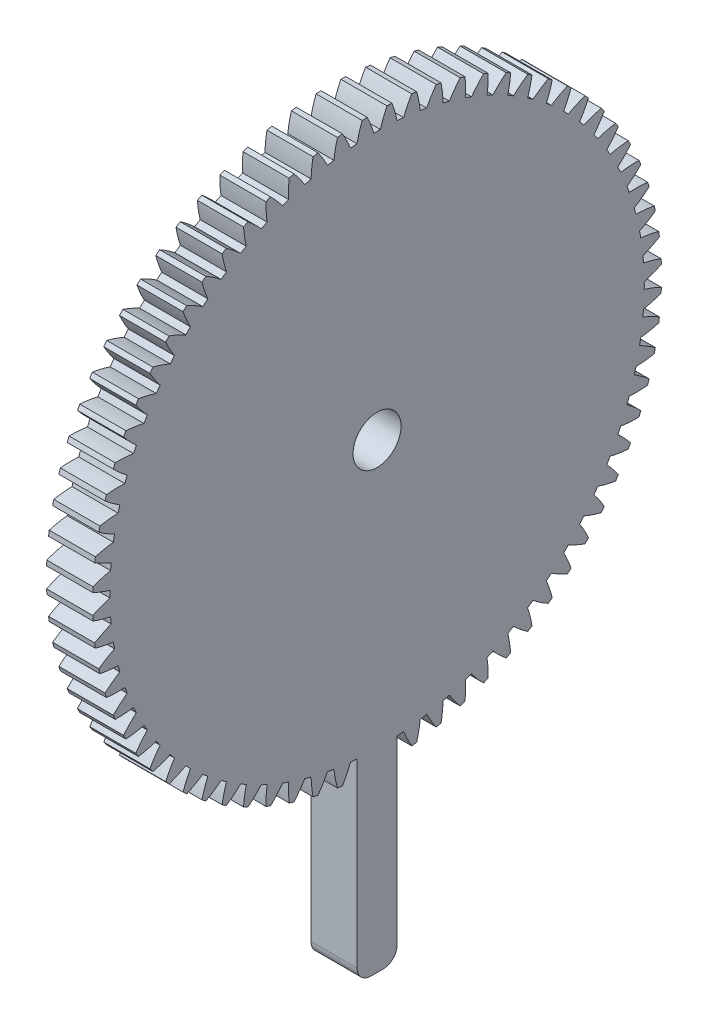
SolidWorks part; units mm, degrees
ref_plane "Front Plane" through (0, 0, 0) normal (0, 0, 1) x (1, 0, 0)
ref_plane "Top Plane" through (0, 0, 0) normal (0, 1, 0) x (1, 0, 0)
ref_plane "Right Plane" through (0, 0, 0) normal (1, 0, 0) x (0, 0, -1)
sketch "Sketch1" plane through (0, 0, 0) normal (0, 0, 1) x (1, 0, 0)
  line L0 (-10, 0) -> (60, 0) construction
  line L1 (0, 0) -> (0, 39.1583)
  line L2 (0, 0) -> (6.35, 0)
  line L3 (6.35, 0) -> (6.35, 39.1583)
  line L4 (6.35, 39.1583) -> (0, 39.1583)
  dimension "Diameter" = 78.3167
  dimension "Thickness" = 6.35
revolve "Revolve1" add sketch "Sketch1" angle 360 about L0
sketch "Sketch2" plane through (0, 0, 0) normal (-1, 0, 0) x (0, 0, 1)
  line L1 (0, 0) -> (0, 107) construction
  line L2 (0, 0) -> (-0.9058, 38.0892) construction
  line L3 (0, 0) -> (-3.3231, 76.1125) construction
  line L4 (-0.9058, 38.0892) -> (-1.6616, 38.0562) construction
  arc A0 (0.4536, 36.7764) -> (-0.4536, 36.7764) centre (0, 0) ccw
  arc A1 (1.3783, 39.1595) -> (-1.3783, 39.1595) centre (0, 0) ccw
  circle A2 centre (0, 0) radius 38.1 construction
  circle A3 centre (0, 0) radius 35.8023 construction
  arc A4 (-0.4536, 36.7764) -> (-1.3783, 39.1595) centre (-15.0738, 32.4744) ccw
  arc A5 (1.3783, 39.1595) -> (0.4536, 36.7764) centre (15.0738, 32.4744) ccw
  arc A6 (2.7534, 36.676) -> (2.0399, 39.1306) centre (-12.1861, 33.6646) ccw
  arc A7 (3.6571, 36.5969) -> (2.7534, 36.676) centre (0, 0) ccw
  arc A8 (4.786, 38.8903) -> (3.6571, 36.5969) centre (17.8467, 31.037) ccw
  arc A9 (4.786, 38.8903) -> (2.0399, 39.1306) centre (0, 0) ccw
  arc A10 (5.9395, 36.2965) -> (5.4426, 38.8039) centre (-9.2057, 34.5986) ccw
  arc A11 (6.8328, 36.1389) -> (5.9395, 36.2965) centre (0, 0) ccw
  arc A12 (8.1573, 38.3252) -> (6.8328, 36.1389) centre (20.4839, 29.3635) ccw
  arc A13 (8.1573, 38.3252) -> (5.4426, 38.8039) centre (0, 0) ccw
  arc A14 (9.0803, 35.6407) -> (8.8039, 38.1819) centre (-6.1552, 35.2692) ccw
  arc A15 (9.9566, 35.4059) -> (9.0803, 35.6407) centre (0, 0) ccw
  arc A16 (11.4665, 37.4684) -> (9.9566, 35.4059) centre (22.9651, 27.4665) ccw
  arc A17 (11.4665, 37.4684) -> (8.8039, 38.1819) centre (0, 0) ccw
  arc A18 (12.152, 34.7136) -> (12.0982, 37.2693) centre (-3.0578, 35.6715) ccw
  arc A19 (13.0045, 34.4034) -> (12.152, 34.7136) centre (0, 0) ccw
  arc A20 (14.6885, 36.3265) -> (13.0045, 34.4034) centre (25.2716, 25.3604) ccw
  arc A21 (14.6885, 36.3265) -> (12.0982, 37.2693) centre (0, 0) ccw
  arc A22 (15.1313, 33.5224) -> (15.3004, 36.073) centre (0.0628, 35.8022) ccw
  arc A23 (15.9535, 33.139) -> (15.1313, 33.5224) centre (0, 0) ccw
  arc A24 (17.7987, 34.9081) -> (15.9535, 33.139) centre (27.3857, 23.0613) ccw
  arc A25 (17.7987, 34.9081) -> (15.3004, 36.073) centre (0, 0) ccw
  arc A26 (17.9954, 32.0761) -> (18.3861, 34.6022) centre (3.1829, 35.6605) ccw
  arc A27 (18.781, 31.6225) -> (17.9954, 32.0761) centre (0, 0) ccw
  arc A28 (20.7734, 33.224) -> (18.781, 31.6225) centre (29.2915, 20.5867) ccw
  arc A29 (20.7734, 33.224) -> (18.3861, 34.6022) centre (0, 0) ccw
  arc A30 (20.7225, 30.3856) -> (21.3319, 32.8681) centre (6.2788, 35.2474) ccw
  arc A31 (21.4656, 29.8653) -> (20.7225, 30.3856) centre (0, 0) ccw
  arc A32 (23.59, 31.287) -> (21.4656, 29.8653) centre (30.9743, 17.9555) ccw
  arc A33 (23.59, 31.287) -> (21.3319, 32.8681) centre (0, 0) ccw
  arc A34 (23.292, 28.4639) -> (24.1154, 30.8838) centre (9.3269, 34.5661) ccw
  arc A35 (23.9869, 27.8808) -> (23.292, 28.4639) centre (0, 0) ccw
  arc A36 (26.227, 29.112) -> (23.9869, 27.8808) centre (32.4213, 15.1876) ccw
  arc A37 (26.227, 29.112) -> (24.1154, 30.8838) centre (0, 0) ccw
  arc A38 (25.6841, 26.3256) -> (26.7154, 28.6645) centre (12.3041, 33.6216) ccw
  arc A39 (26.3256, 25.6841) -> (25.6841, 26.3256) centre (0, 0) ccw
  arc A40 (28.6645, 26.7154) -> (26.3256, 25.6841) centre (33.6216, 12.3041) ccw
  arc A41 (28.6645, 26.7154) -> (26.7154, 28.6645) centre (0, 0) ccw
  arc A42 (27.8808, 23.9869) -> (29.112, 26.227) centre (15.1876, 32.4213) ccw
  arc A43 (28.4639, 23.292) -> (27.8808, 23.9869) centre (0, 0) ccw
  arc A44 (30.8838, 24.1154) -> (28.4639, 23.292) centre (34.5661, 9.3269) ccw
  arc A45 (30.8838, 24.1154) -> (29.112, 26.227) centre (0, 0) ccw
  arc A46 (29.8653, 21.4656) -> (31.287, 23.59) centre (17.9555, 30.9743) ccw
  arc A47 (30.3856, 20.7225) -> (29.8653, 21.4656) centre (0, 0) ccw
  arc A48 (32.8681, 21.3319) -> (30.3856, 20.7225) centre (35.2474, 6.2788) ccw
  arc A49 (32.8681, 21.3319) -> (31.287, 23.59) centre (0, 0) ccw
  arc A50 (31.6225, 18.781) -> (33.224, 20.7734) centre (20.5867, 29.2915) ccw
  arc A51 (32.0761, 17.9954) -> (31.6225, 18.781) centre (0, 0) ccw
  arc A52 (34.6022, 18.3861) -> (32.0761, 17.9954) centre (35.6605, 3.1829) ccw
  arc A53 (34.6022, 18.3861) -> (33.224, 20.7734) centre (0, 0) ccw
  arc A54 (33.139, 15.9535) -> (34.9081, 17.7987) centre (23.0613, 27.3857) ccw
  arc A55 (33.5224, 15.1313) -> (33.139, 15.9535) centre (0, 0) ccw
  arc A56 (36.073, 15.3004) -> (33.5224, 15.1313) centre (35.8022, 0.0628) ccw
  arc A57 (36.073, 15.3004) -> (34.9081, 17.7987) centre (0, 0) ccw
  arc A58 (34.4034, 13.0045) -> (36.3265, 14.6885) centre (25.3604, 25.2716) ccw
  arc A59 (34.7136, 12.152) -> (34.4034, 13.0045) centre (0, 0) ccw
  arc A60 (37.2693, 12.0982) -> (34.7136, 12.152) centre (35.6715, -3.0578) ccw
  arc A61 (37.2693, 12.0982) -> (36.3265, 14.6885) centre (0, 0) ccw
  arc A62 (35.4059, 9.9566) -> (37.4684, 11.4665) centre (27.4665, 22.9651) ccw
  arc A63 (35.6407, 9.0803) -> (35.4059, 9.9566) centre (0, 0) ccw
  arc A64 (38.1819, 8.8039) -> (35.6407, 9.0803) centre (35.2692, -6.1552) ccw
  arc A65 (38.1819, 8.8039) -> (37.4684, 11.4665) centre (0, 0) ccw
  arc A66 (36.1389, 6.8328) -> (38.3252, 8.1573) centre (29.3635, 20.4839) ccw
  arc A67 (36.2965, 5.9395) -> (36.1389, 6.8328) centre (0, 0) ccw
  arc A68 (38.8039, 5.4426) -> (36.2965, 5.9395) centre (34.5986, -9.2057) ccw
  arc A69 (38.8039, 5.4426) -> (38.3252, 8.1573) centre (0, 0) ccw
  arc A70 (36.5969, 3.6571) -> (38.8903, 4.786) centre (31.037, 17.8467) ccw
  arc A71 (36.676, 2.7534) -> (36.5969, 3.6571) centre (0, 0) ccw
  arc A72 (39.1306, 2.0399) -> (36.676, 2.7534) centre (33.6646, -12.1861) ccw
  arc A73 (39.1306, 2.0399) -> (38.8903, 4.786) centre (0, 0) ccw
  arc A74 (36.7764, 0.4536) -> (39.1595, 1.3783) centre (32.4744, 15.0738) ccw
  arc A75 (36.7764, -0.4536) -> (36.7764, 0.4536) centre (0, 0) ccw
  arc A76 (39.1595, -1.3783) -> (36.7764, -0.4536) centre (32.4744, -15.0738) ccw
  arc A77 (39.1595, -1.3783) -> (39.1595, 1.3783) centre (0, 0) ccw
  arc A78 (36.676, -2.7534) -> (39.1306, -2.0399) centre (33.6646, 12.1861) ccw
  arc A79 (36.5969, -3.6571) -> (36.676, -2.7534) centre (0, 0) ccw
  arc A80 (38.8903, -4.786) -> (36.5969, -3.6571) centre (31.037, -17.8467) ccw
  arc A81 (38.8903, -4.786) -> (39.1306, -2.0399) centre (0, 0) ccw
  arc A82 (36.2965, -5.9395) -> (38.8039, -5.4426) centre (34.5986, 9.2057) ccw
  arc A83 (36.1389, -6.8328) -> (36.2965, -5.9395) centre (0, 0) ccw
  arc A84 (38.3252, -8.1573) -> (36.1389, -6.8328) centre (29.3635, -20.4839) ccw
  arc A85 (38.3252, -8.1573) -> (38.8039, -5.4426) centre (0, 0) ccw
  arc A86 (35.6407, -9.0803) -> (38.1819, -8.8039) centre (35.2692, 6.1552) ccw
  arc A87 (35.4059, -9.9566) -> (35.6407, -9.0803) centre (0, 0) ccw
  arc A88 (37.4684, -11.4665) -> (35.4059, -9.9566) centre (27.4665, -22.9651) ccw
  arc A89 (37.4684, -11.4665) -> (38.1819, -8.8039) centre (0, 0) ccw
  arc A90 (34.7136, -12.152) -> (37.2693, -12.0982) centre (35.6715, 3.0578) ccw
  arc A91 (34.4034, -13.0045) -> (34.7136, -12.152) centre (0, 0) ccw
  arc A92 (36.3265, -14.6885) -> (34.4034, -13.0045) centre (25.3604, -25.2716) ccw
  arc A93 (36.3265, -14.6885) -> (37.2693, -12.0982) centre (0, 0) ccw
  arc A94 (33.5224, -15.1313) -> (36.073, -15.3004) centre (35.8022, -0.0628) ccw
  arc A95 (33.139, -15.9535) -> (33.5224, -15.1313) centre (0, 0) ccw
  arc A96 (34.9081, -17.7987) -> (33.139, -15.9535) centre (23.0613, -27.3857) ccw
  arc A97 (34.9081, -17.7987) -> (36.073, -15.3004) centre (0, 0) ccw
  arc A98 (32.0761, -17.9954) -> (34.6022, -18.3861) centre (35.6605, -3.1829) ccw
  arc A99 (31.6225, -18.781) -> (32.0761, -17.9954) centre (0, 0) ccw
  arc A100 (33.224, -20.7734) -> (31.6225, -18.781) centre (20.5867, -29.2915) ccw
  arc A101 (33.224, -20.7734) -> (34.6022, -18.3861) centre (0, 0) ccw
  arc A102 (30.3856, -20.7225) -> (32.8681, -21.3319) centre (35.2474, -6.2788) ccw
  arc A103 (29.8653, -21.4656) -> (30.3856, -20.7225) centre (0, 0) ccw
  arc A104 (31.287, -23.59) -> (29.8653, -21.4656) centre (17.9555, -30.9743) ccw
  arc A105 (31.287, -23.59) -> (32.8681, -21.3319) centre (0, 0) ccw
  arc A106 (28.4639, -23.292) -> (30.8838, -24.1154) centre (34.5661, -9.3269) ccw
  arc A107 (27.8808, -23.9869) -> (28.4639, -23.292) centre (0, 0) ccw
  arc A108 (29.112, -26.227) -> (27.8808, -23.9869) centre (15.1876, -32.4213) ccw
  arc A109 (29.112, -26.227) -> (30.8838, -24.1154) centre (0, 0) ccw
  arc A110 (26.3256, -25.6841) -> (28.6645, -26.7154) centre (33.6216, -12.3041) ccw
  arc A111 (25.6841, -26.3256) -> (26.3256, -25.6841) centre (0, 0) ccw
  arc A112 (26.7154, -28.6645) -> (25.6841, -26.3256) centre (12.3041, -33.6216) ccw
  arc A113 (26.7154, -28.6645) -> (28.6645, -26.7154) centre (0, 0) ccw
  arc A114 (23.9869, -27.8808) -> (26.227, -29.112) centre (32.4213, -15.1876) ccw
  arc A115 (23.292, -28.4639) -> (23.9869, -27.8808) centre (0, 0) ccw
  arc A116 (24.1154, -30.8838) -> (23.292, -28.4639) centre (9.3269, -34.5661) ccw
  arc A117 (24.1154, -30.8838) -> (26.227, -29.112) centre (0, 0) ccw
  arc A118 (21.4656, -29.8653) -> (23.59, -31.287) centre (30.9743, -17.9555) ccw
  arc A119 (20.7225, -30.3856) -> (21.4656, -29.8653) centre (0, 0) ccw
  arc A120 (21.3319, -32.8681) -> (20.7225, -30.3856) centre (6.2788, -35.2474) ccw
  arc A121 (21.3319, -32.8681) -> (23.59, -31.287) centre (0, 0) ccw
  arc A122 (18.781, -31.6225) -> (20.7734, -33.224) centre (29.2915, -20.5867) ccw
  arc A123 (17.9954, -32.0761) -> (18.781, -31.6225) centre (0, 0) ccw
  arc A124 (18.3861, -34.6022) -> (17.9954, -32.0761) centre (3.1829, -35.6605) ccw
  arc A125 (18.3861, -34.6022) -> (20.7734, -33.224) centre (0, 0) ccw
  arc A126 (15.9535, -33.139) -> (17.7987, -34.9081) centre (27.3857, -23.0613) ccw
  arc A127 (15.1313, -33.5224) -> (15.9535, -33.139) centre (0, 0) ccw
  arc A128 (15.3004, -36.073) -> (15.1313, -33.5224) centre (0.0628, -35.8022) ccw
  arc A129 (15.3004, -36.073) -> (17.7987, -34.9081) centre (0, 0) ccw
  arc A130 (13.0045, -34.4034) -> (14.6885, -36.3265) centre (25.2716, -25.3604) ccw
  arc A131 (12.152, -34.7136) -> (13.0045, -34.4034) centre (0, 0) ccw
  arc A132 (12.0982, -37.2693) -> (12.152, -34.7136) centre (-3.0578, -35.6715) ccw
  arc A133 (12.0982, -37.2693) -> (14.6885, -36.3265) centre (0, 0) ccw
  arc A134 (9.9566, -35.4059) -> (11.4665, -37.4684) centre (22.9651, -27.4665) ccw
  arc A135 (9.0803, -35.6407) -> (9.9566, -35.4059) centre (0, 0) ccw
  arc A136 (8.8039, -38.1819) -> (9.0803, -35.6407) centre (-6.1552, -35.2692) ccw
  arc A137 (8.8039, -38.1819) -> (11.4665, -37.4684) centre (0, 0) ccw
  arc A138 (6.8328, -36.1389) -> (8.1573, -38.3252) centre (20.4839, -29.3635) ccw
  arc A139 (5.9395, -36.2965) -> (6.8328, -36.1389) centre (0, 0) ccw
  arc A140 (5.4426, -38.8039) -> (5.9395, -36.2965) centre (-9.2057, -34.5986) ccw
  arc A141 (5.4426, -38.8039) -> (8.1573, -38.3252) centre (0, 0) ccw
  arc A142 (3.6571, -36.5969) -> (4.786, -38.8903) centre (17.8467, -31.037) ccw
  arc A143 (2.7534, -36.676) -> (3.6571, -36.5969) centre (0, 0) ccw
  arc A144 (2.0399, -39.1306) -> (2.7534, -36.676) centre (-12.1861, -33.6646) ccw
  arc A145 (2.0399, -39.1306) -> (4.786, -38.8903) centre (0, 0) ccw
  arc A146 (0.4536, -36.7764) -> (1.3783, -39.1595) centre (15.0738, -32.4744) ccw
  arc A147 (-0.4536, -36.7764) -> (0.4536, -36.7764) centre (0, 0) ccw
  arc A148 (-1.3783, -39.1595) -> (-0.4536, -36.7764) centre (-15.0738, -32.4744) ccw
  arc A149 (-1.3783, -39.1595) -> (1.3783, -39.1595) centre (0, 0) ccw
  arc A150 (-2.7534, -36.676) -> (-2.0399, -39.1306) centre (12.1861, -33.6646) ccw
  arc A151 (-3.6571, -36.5969) -> (-2.7534, -36.676) centre (0, 0) ccw
  arc A152 (-4.786, -38.8903) -> (-3.6571, -36.5969) centre (-17.8467, -31.037) ccw
  arc A153 (-4.786, -38.8903) -> (-2.0399, -39.1306) centre (0, 0) ccw
  arc A154 (-5.9395, -36.2965) -> (-5.4426, -38.8039) centre (9.2057, -34.5986) ccw
  arc A155 (-6.8328, -36.1389) -> (-5.9395, -36.2965) centre (0, 0) ccw
  arc A156 (-8.1573, -38.3252) -> (-6.8328, -36.1389) centre (-20.4839, -29.3635) ccw
  arc A157 (-8.1573, -38.3252) -> (-5.4426, -38.8039) centre (0, 0) ccw
  arc A158 (-9.0803, -35.6407) -> (-8.8039, -38.1819) centre (6.1552, -35.2692) ccw
  arc A159 (-9.9566, -35.4059) -> (-9.0803, -35.6407) centre (0, 0) ccw
  arc A160 (-11.4665, -37.4684) -> (-9.9566, -35.4059) centre (-22.9651, -27.4665) ccw
  arc A161 (-11.4665, -37.4684) -> (-8.8039, -38.1819) centre (0, 0) ccw
  arc A162 (-12.152, -34.7136) -> (-12.0982, -37.2693) centre (3.0578, -35.6715) ccw
  arc A163 (-13.0045, -34.4034) -> (-12.152, -34.7136) centre (0, 0) ccw
  arc A164 (-14.6885, -36.3265) -> (-13.0045, -34.4034) centre (-25.2716, -25.3604) ccw
  arc A165 (-14.6885, -36.3265) -> (-12.0982, -37.2693) centre (0, 0) ccw
  arc A166 (-15.1313, -33.5224) -> (-15.3004, -36.073) centre (-0.0628, -35.8022) ccw
  arc A167 (-15.9535, -33.139) -> (-15.1313, -33.5224) centre (0, 0) ccw
  arc A168 (-17.7987, -34.9081) -> (-15.9535, -33.139) centre (-27.3857, -23.0613) ccw
  arc A169 (-17.7987, -34.9081) -> (-15.3004, -36.073) centre (0, 0) ccw
  arc A170 (-17.9954, -32.0761) -> (-18.3861, -34.6022) centre (-3.1829, -35.6605) ccw
  arc A171 (-18.781, -31.6225) -> (-17.9954, -32.0761) centre (0, 0) ccw
  arc A172 (-20.7734, -33.224) -> (-18.781, -31.6225) centre (-29.2915, -20.5867) ccw
  arc A173 (-20.7734, -33.224) -> (-18.3861, -34.6022) centre (0, 0) ccw
  arc A174 (-20.7225, -30.3856) -> (-21.3319, -32.8681) centre (-6.2788, -35.2474) ccw
  arc A175 (-21.4656, -29.8653) -> (-20.7225, -30.3856) centre (0, 0) ccw
  arc A176 (-23.59, -31.287) -> (-21.4656, -29.8653) centre (-30.9743, -17.9555) ccw
  arc A177 (-23.59, -31.287) -> (-21.3319, -32.8681) centre (0, 0) ccw
  arc A178 (-23.292, -28.4639) -> (-24.1154, -30.8838) centre (-9.3269, -34.5661) ccw
  arc A179 (-23.9869, -27.8808) -> (-23.292, -28.4639) centre (0, 0) ccw
  arc A180 (-26.227, -29.112) -> (-23.9869, -27.8808) centre (-32.4213, -15.1876) ccw
  arc A181 (-26.227, -29.112) -> (-24.1154, -30.8838) centre (0, 0) ccw
  arc A182 (-25.6841, -26.3256) -> (-26.7154, -28.6645) centre (-12.3041, -33.6216) ccw
  arc A183 (-26.3256, -25.6841) -> (-25.6841, -26.3256) centre (0, 0) ccw
  arc A184 (-28.6645, -26.7154) -> (-26.3256, -25.6841) centre (-33.6216, -12.3041) ccw
  arc A185 (-28.6645, -26.7154) -> (-26.7154, -28.6645) centre (0, 0) ccw
  arc A186 (-27.8808, -23.9869) -> (-29.112, -26.227) centre (-15.1876, -32.4213) ccw
  arc A187 (-28.4639, -23.292) -> (-27.8808, -23.9869) centre (0, 0) ccw
  arc A188 (-30.8838, -24.1154) -> (-28.4639, -23.292) centre (-34.5661, -9.3269) ccw
  arc A189 (-30.8838, -24.1154) -> (-29.112, -26.227) centre (0, 0) ccw
  arc A190 (-29.8653, -21.4656) -> (-31.287, -23.59) centre (-17.9555, -30.9743) ccw
  arc A191 (-30.3856, -20.7225) -> (-29.8653, -21.4656) centre (0, 0) ccw
  arc A192 (-32.8681, -21.3319) -> (-30.3856, -20.7225) centre (-35.2474, -6.2788) ccw
  arc A193 (-32.8681, -21.3319) -> (-31.287, -23.59) centre (0, 0) ccw
  arc A194 (-31.6225, -18.781) -> (-33.224, -20.7734) centre (-20.5867, -29.2915) ccw
  arc A195 (-32.0761, -17.9954) -> (-31.6225, -18.781) centre (0, 0) ccw
  arc A196 (-34.6022, -18.3861) -> (-32.0761, -17.9954) centre (-35.6605, -3.1829) ccw
  arc A197 (-34.6022, -18.3861) -> (-33.224, -20.7734) centre (0, 0) ccw
  arc A198 (-33.139, -15.9535) -> (-34.9081, -17.7987) centre (-23.0613, -27.3857) ccw
  arc A199 (-33.5224, -15.1313) -> (-33.139, -15.9535) centre (0, 0) ccw
  arc A200 (-36.073, -15.3004) -> (-33.5224, -15.1313) centre (-35.8022, -0.0628) ccw
  arc A201 (-36.073, -15.3004) -> (-34.9081, -17.7987) centre (0, 0) ccw
  arc A202 (-34.4034, -13.0045) -> (-36.3265, -14.6885) centre (-25.3604, -25.2716) ccw
  arc A203 (-34.7136, -12.152) -> (-34.4034, -13.0045) centre (0, 0) ccw
  arc A204 (-37.2693, -12.0982) -> (-34.7136, -12.152) centre (-35.6715, 3.0578) ccw
  arc A205 (-37.2693, -12.0982) -> (-36.3265, -14.6885) centre (0, 0) ccw
  arc A206 (-35.4059, -9.9566) -> (-37.4684, -11.4665) centre (-27.4665, -22.9651) ccw
  arc A207 (-35.6407, -9.0803) -> (-35.4059, -9.9566) centre (0, 0) ccw
  arc A208 (-38.1819, -8.8039) -> (-35.6407, -9.0803) centre (-35.2692, 6.1552) ccw
  arc A209 (-38.1819, -8.8039) -> (-37.4684, -11.4665) centre (0, 0) ccw
  arc A210 (-36.1389, -6.8328) -> (-38.3252, -8.1573) centre (-29.3635, -20.4839) ccw
  arc A211 (-36.2965, -5.9395) -> (-36.1389, -6.8328) centre (0, 0) ccw
  arc A212 (-38.8039, -5.4426) -> (-36.2965, -5.9395) centre (-34.5986, 9.2057) ccw
  arc A213 (-38.8039, -5.4426) -> (-38.3252, -8.1573) centre (0, 0) ccw
  arc A214 (-36.5969, -3.6571) -> (-38.8903, -4.786) centre (-31.037, -17.8467) ccw
  arc A215 (-36.676, -2.7534) -> (-36.5969, -3.6571) centre (0, 0) ccw
  arc A216 (-39.1306, -2.0399) -> (-36.676, -2.7534) centre (-33.6646, 12.1861) ccw
  arc A217 (-39.1306, -2.0399) -> (-38.8903, -4.786) centre (0, 0) ccw
  arc A218 (-36.7764, -0.4536) -> (-39.1595, -1.3783) centre (-32.4744, -15.0738) ccw
  arc A219 (-36.7764, 0.4536) -> (-36.7764, -0.4536) centre (0, 0) ccw
  arc A220 (-39.1595, 1.3783) -> (-36.7764, 0.4536) centre (-32.4744, 15.0738) ccw
  arc A221 (-39.1595, 1.3783) -> (-39.1595, -1.3783) centre (0, 0) ccw
  arc A222 (-36.676, 2.7534) -> (-39.1306, 2.0399) centre (-33.6646, -12.1861) ccw
  arc A223 (-36.5969, 3.6571) -> (-36.676, 2.7534) centre (0, 0) ccw
  arc A224 (-38.8903, 4.786) -> (-36.5969, 3.6571) centre (-31.037, 17.8467) ccw
  arc A225 (-38.8903, 4.786) -> (-39.1306, 2.0399) centre (0, 0) ccw
  arc A226 (-36.2965, 5.9395) -> (-38.8039, 5.4426) centre (-34.5986, -9.2057) ccw
  arc A227 (-36.1389, 6.8328) -> (-36.2965, 5.9395) centre (0, 0) ccw
  arc A228 (-38.3252, 8.1573) -> (-36.1389, 6.8328) centre (-29.3635, 20.4839) ccw
  arc A229 (-38.3252, 8.1573) -> (-38.8039, 5.4426) centre (0, 0) ccw
  arc A230 (-35.6407, 9.0803) -> (-38.1819, 8.8039) centre (-35.2692, -6.1552) ccw
  arc A231 (-35.4059, 9.9566) -> (-35.6407, 9.0803) centre (0, 0) ccw
  arc A232 (-37.4684, 11.4665) -> (-35.4059, 9.9566) centre (-27.4665, 22.9651) ccw
  arc A233 (-37.4684, 11.4665) -> (-38.1819, 8.8039) centre (0, 0) ccw
  arc A234 (-34.7136, 12.152) -> (-37.2693, 12.0982) centre (-35.6715, -3.0578) ccw
  arc A235 (-34.4034, 13.0045) -> (-34.7136, 12.152) centre (0, 0) ccw
  arc A236 (-36.3265, 14.6885) -> (-34.4034, 13.0045) centre (-25.3604, 25.2716) ccw
  arc A237 (-36.3265, 14.6885) -> (-37.2693, 12.0982) centre (0, 0) ccw
  arc A238 (-33.5224, 15.1313) -> (-36.073, 15.3004) centre (-35.8022, 0.0628) ccw
  arc A239 (-33.139, 15.9535) -> (-33.5224, 15.1313) centre (0, 0) ccw
  arc A240 (-34.9081, 17.7987) -> (-33.139, 15.9535) centre (-23.0613, 27.3857) ccw
  arc A241 (-34.9081, 17.7987) -> (-36.073, 15.3004) centre (0, 0) ccw
  arc A242 (-32.0761, 17.9954) -> (-34.6022, 18.3861) centre (-35.6605, 3.1829) ccw
  arc A243 (-31.6225, 18.781) -> (-32.0761, 17.9954) centre (0, 0) ccw
  arc A244 (-33.224, 20.7734) -> (-31.6225, 18.781) centre (-20.5867, 29.2915) ccw
  arc A245 (-33.224, 20.7734) -> (-34.6022, 18.3861) centre (0, 0) ccw
  arc A246 (-30.3856, 20.7225) -> (-32.8681, 21.3319) centre (-35.2474, 6.2788) ccw
  arc A247 (-29.8653, 21.4656) -> (-30.3856, 20.7225) centre (0, 0) ccw
  arc A248 (-31.287, 23.59) -> (-29.8653, 21.4656) centre (-17.9555, 30.9743) ccw
  arc A249 (-31.287, 23.59) -> (-32.8681, 21.3319) centre (0, 0) ccw
  arc A250 (-28.4639, 23.292) -> (-30.8838, 24.1154) centre (-34.5661, 9.3269) ccw
  arc A251 (-27.8808, 23.9869) -> (-28.4639, 23.292) centre (0, 0) ccw
  arc A252 (-29.112, 26.227) -> (-27.8808, 23.9869) centre (-15.1876, 32.4213) ccw
  arc A253 (-29.112, 26.227) -> (-30.8838, 24.1154) centre (0, 0) ccw
  arc A254 (-26.3256, 25.6841) -> (-28.6645, 26.7154) centre (-33.6216, 12.3041) ccw
  arc A255 (-25.6841, 26.3256) -> (-26.3256, 25.6841) centre (0, 0) ccw
  arc A256 (-26.7154, 28.6645) -> (-25.6841, 26.3256) centre (-12.3041, 33.6216) ccw
  arc A257 (-26.7154, 28.6645) -> (-28.6645, 26.7154) centre (0, 0) ccw
  arc A258 (-23.9869, 27.8808) -> (-26.227, 29.112) centre (-32.4213, 15.1876) ccw
  arc A259 (-23.292, 28.4639) -> (-23.9869, 27.8808) centre (0, 0) ccw
  arc A260 (-24.1154, 30.8838) -> (-23.292, 28.4639) centre (-9.3269, 34.5661) ccw
  arc A261 (-24.1154, 30.8838) -> (-26.227, 29.112) centre (0, 0) ccw
  arc A262 (-21.4656, 29.8653) -> (-23.59, 31.287) centre (-30.9743, 17.9555) ccw
  arc A263 (-20.7225, 30.3856) -> (-21.4656, 29.8653) centre (0, 0) ccw
  arc A264 (-21.3319, 32.8681) -> (-20.7225, 30.3856) centre (-6.2788, 35.2474) ccw
  arc A265 (-21.3319, 32.8681) -> (-23.59, 31.287) centre (0, 0) ccw
  arc A266 (-18.781, 31.6225) -> (-20.7734, 33.224) centre (-29.2915, 20.5867) ccw
  arc A267 (-17.9954, 32.0761) -> (-18.781, 31.6225) centre (0, 0) ccw
  arc A268 (-18.3861, 34.6022) -> (-17.9954, 32.0761) centre (-3.1829, 35.6605) ccw
  arc A269 (-18.3861, 34.6022) -> (-20.7734, 33.224) centre (0, 0) ccw
  arc A270 (-15.9535, 33.139) -> (-17.7987, 34.9081) centre (-27.3857, 23.0613) ccw
  arc A271 (-15.1313, 33.5224) -> (-15.9535, 33.139) centre (0, 0) ccw
  arc A272 (-15.3004, 36.073) -> (-15.1313, 33.5224) centre (-0.0628, 35.8022) ccw
  arc A273 (-15.3004, 36.073) -> (-17.7987, 34.9081) centre (0, 0) ccw
  arc A274 (-13.0045, 34.4034) -> (-14.6885, 36.3265) centre (-25.2716, 25.3604) ccw
  arc A275 (-12.152, 34.7136) -> (-13.0045, 34.4034) centre (0, 0) ccw
  arc A276 (-12.0982, 37.2693) -> (-12.152, 34.7136) centre (3.0578, 35.6715) ccw
  arc A277 (-12.0982, 37.2693) -> (-14.6885, 36.3265) centre (0, 0) ccw
  arc A278 (-9.9566, 35.4059) -> (-11.4665, 37.4684) centre (-22.9651, 27.4665) ccw
  arc A279 (-9.0803, 35.6407) -> (-9.9566, 35.4059) centre (0, 0) ccw
  arc A280 (-8.8039, 38.1819) -> (-9.0803, 35.6407) centre (6.1552, 35.2692) ccw
  arc A281 (-8.8039, 38.1819) -> (-11.4665, 37.4684) centre (0, 0) ccw
  arc A282 (-6.8328, 36.1389) -> (-8.1573, 38.3252) centre (-20.4839, 29.3635) ccw
  arc A283 (-5.9395, 36.2965) -> (-6.8328, 36.1389) centre (0, 0) ccw
  arc A284 (-5.4426, 38.8039) -> (-5.9395, 36.2965) centre (9.2057, 34.5986) ccw
  arc A285 (-5.4426, 38.8039) -> (-8.1573, 38.3252) centre (0, 0) ccw
  arc A286 (-3.6571, 36.5969) -> (-4.786, 38.8903) centre (-17.8467, 31.037) ccw
  arc A287 (-2.7534, 36.676) -> (-3.6571, 36.5969) centre (0, 0) ccw
  arc A288 (-2.0399, 39.1306) -> (-2.7534, 36.676) centre (12.1861, 33.6646) ccw
  arc A289 (-2.0399, 39.1306) -> (-4.786, 38.8903) centre (0, 0) ccw
  point P444 (0, 0)
  dimension "Root_dia" = 73.5584
  dimension "Overcut_dia" = 78.3675
  dimension "Pitch_dia" = 76.2
  dimension "Base_dia" = 71.6046
  dimension "Flank_rad" = 15.24
  dimension "Half_ang" = 2.5
  dimension "Half_CT" = 0.7565
extrude "Cut-Extrude1" cut sketch "Sketch2" against normal through all
sketch "Sketch5" plane through (0, 0, 0) normal (-1, 0, 0) x (0, 0, 1)
  circle A0 centre (0, 0) radius 3.302
  dimension "D1" = 6.604
extrude "Cut-Extrude3" cut sketch "Sketch5" against normal through all contours A0
sketch "Sketch6" plane through (0, 0, 0) normal (-1, 0, 0) x (0, 0, 1)
  line L0 (0, 0) -> (0, -63.5) construction
  line L2 (-0.8484, -63.5) -> (0.8484, -63.5)
  line L3 (-2.7534, -61.595) -> (-2.7534, -35.56)
  line L4 (-2.7534, -35.56) -> (2.7534, -35.56)
  line L5 (2.7534, -61.595) -> (2.7534, -35.56)
  line L6 (-2.7534, -63.5) -> (2.7534, -35.56) construction
  line L7 (-2.7534, -35.56) -> (2.7534, -63.5) construction
  arc A0 (0.8484, -63.5) -> (2.7534, -61.595) centre (0.8484, -61.595) ccw
  arc A1 (-0.8484, -63.5) -> (-2.7534, -61.595) centre (-0.8484, -61.595) cw
  point P3 (0, -49.53)
  point P8 (0, 0)
  dimension "D3" = 1.905
  dimension "D1" = 63.5
  dimension "D2" = 35.56
extrude "Boss-Extrude1" add sketch "Sketch6" against normal up to surface (6.35 mm away) up to face at (6.35, 0, 3.302)
